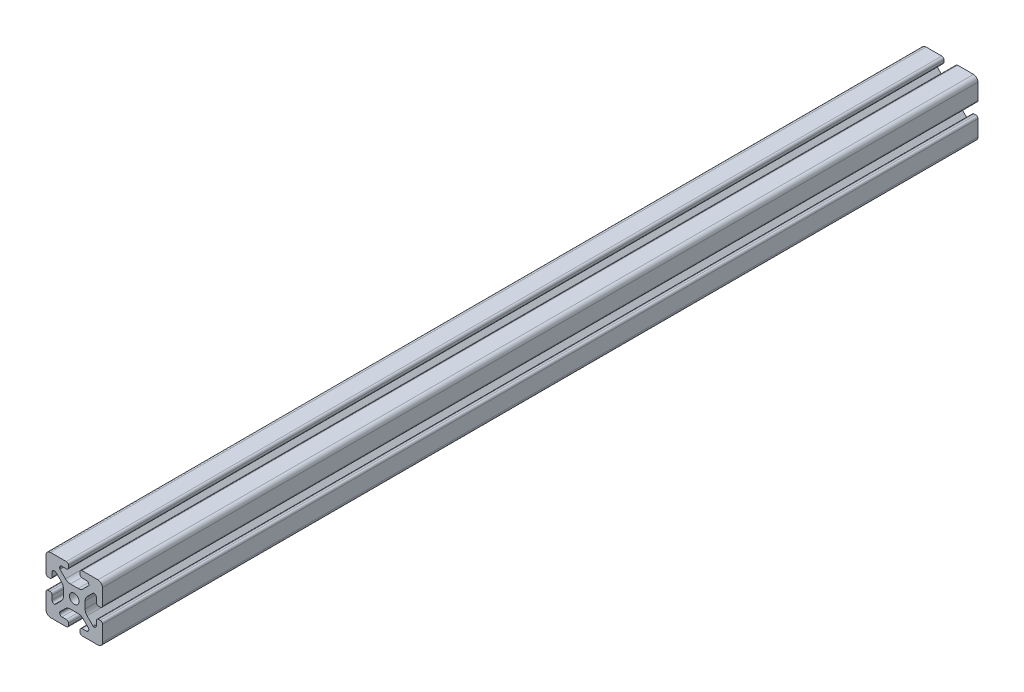
SolidWorks part; units mm, degrees
material "6061 Alloy"
ref_plane "Front Plane" through (0, 0, 0) normal (0, 0, 1) x (1, 0, 0)
ref_plane "Top Plane" through (0, 0, 0) normal (0, 1, 0) x (1, 0, 0)
ref_plane "Right Plane" through (0, 0, 0) normal (1, 0, 0) x (0, 0, -1)
sketch "Sketch1" plane through (0, 0, 0) normal (0, 0, 1) x (1, 0, 0)
  line L0 (0, 19.7407) -> (0, -19.7407) construction
  line L1 (19.0335, 0) -> (-20.7246, 0) construction
  line L2 (-8.715, -15.5246) -> (-5.63, -15.5246)
  line L3 (-10.285, -13.9546) -> (-10.285, -13.4925)
  line L4 (-6.2171, -9.1098) -> (-10.0624, -12.9551)
  line L5 (2.7773, -7.685) -> (-2.7773, -7.685)
  line L6 (10.0624, -12.9551) -> (6.2171, -9.1098)
  line L7 (10.285, -13.9546) -> (10.285, -13.4925)
  line L8 (5.63, -15.5246) -> (8.715, -15.5246)
  line L9 (4.06, -18.43) -> (4.06, -17.0946)
  line L10 (-4.06, -18.43) -> (-4.06, -17.0946)
  line L11 (15.68, -8.7154) -> (15.68, -5.63)
  line L12 (-14.11, -10.2854) -> (-13.8169, -10.2854)
  line L13 (20, -16.83) -> (20, -5.63)
  line L14 (20, 5.63) -> (20, 13.0011)
  line L15 (-16.83, 20) -> (-5.63, 20)
  line L16 (5.63, 20) -> (12.9796, 20)
  line L18 (-8.715, 15.5246) -> (-5.63, 15.5246)
  line L19 (-20, -17.0184) -> (-20, -5.7579)
  line L20 (-20, 5.573) -> (-20, 13.0045)
  line L21 (-15.68, -8.7154) -> (-15.68, -5.7579)
  line L23 (-16.6746, -20) -> (-5.63, -20)
  line L24 (5.63, -20) -> (13, -20)
  line L53 (14.11, -10.2854) -> (13.6201, -10.2854)
  line L54 (13.1637, -9.947) -> (9.0762, -5.8595)
  line L55 (7.685, -2.5008) -> (7.685, 2.5008)
  line L56 (9.0762, 5.8595) -> (13.2795, 10.0628)
  line L57 (13.8169, 10.2854) -> (14.11, 10.2854)
  line L58 (15.68, 8.7154) -> (15.68, 5.63)
  line L59 (17.25, 4.06) -> (18.43, 4.06)
  line L61 (20, 13.0011) -> (20, 16.83)
  line L62 (16.83, 20) -> (12.9796, 20)
  line L64 (4.06, 18.43) -> (4.06, 17.0946)
  line L65 (5.63, 15.5246) -> (8.715, 15.5246)
  line L66 (10.285, 13.9546) -> (10.285, 13.4925)
  line L67 (10.0624, 12.9551) -> (6.2171, 9.1098)
  line L68 (2.7773, 7.685) -> (-2.7773, 7.685)
  line L69 (-6.2171, 9.1098) -> (-10.0624, 12.9551)
  line L70 (-10.285, 13.4925) -> (-10.285, 13.9546)
  line L72 (-4.06, 17.0946) -> (-4.06, 18.43)
  line L75 (-20, 16.83) -> (-20, 13.0045)
  line L77 (-18.43, 4.003) -> (-17.25, 4.003)
  line L78 (-15.68, 5.573) -> (-15.68, 8.4757)
  line L79 (-14.0552, 10.0447) -> (-13.7199, 10.033)
  line L80 (-13.0405, 9.8238) -> (-9.0762, 5.8595)
  line L81 (-7.685, 2.5008) -> (-7.685, -2.5008)
  line L82 (-9.0762, -5.8595) -> (-13.2795, -10.0628)
  line L85 (-17.25, -4.1204) -> (-18.43, -4.1204)
  line L100 (13, -20) -> (16.83, -20)
  line L103 (18.43, -4.06) -> (17.25, -4.06)
  arc A0 (-5.63, -15.5246) -> (-4.06, -17.0946) centre (-5.63, -17.0946) cw
  arc A1 (-8.715, -15.5246) -> (-10.285, -13.9546) centre (-8.715, -13.9546) cw
  arc A2 (-10.285, -13.4925) -> (-10.0624, -12.9551) centre (-9.525, -13.4925) cw
  arc A3 (-6.2171, -9.1098) -> (-2.7773, -7.685) centre (-2.7773, -12.5496) cw
  arc A4 (2.7773, -7.685) -> (6.2171, -9.1098) centre (2.7773, -12.5496) cw
  arc A5 (10.0624, -12.9551) -> (10.285, -13.4925) centre (9.525, -13.4925) cw
  arc A6 (10.285, -13.9546) -> (8.715, -15.5246) centre (8.715, -13.9546) cw
  arc A7 (4.06, -17.0946) -> (5.63, -15.5246) centre (5.63, -17.0946) cw
  arc A8 (5.63, -20) -> (4.06, -18.43) centre (5.63, -18.43) cw
  arc A9 (-4.06, -18.43) -> (-5.63, -20) centre (-5.63, -18.43) cw
  circle A45 centre (0, 0) radius 3.4
  arc A46 (17.25, -4.06) -> (15.68, -5.63) centre (17.25, -5.63) ccw
  arc A47 (14.11, -10.2854) -> (15.68, -8.7154) centre (14.11, -8.7154) ccw
  arc A48 (13.1637, -9.947) -> (13.6201, -10.2854) centre (13.8117, -9.55) ccw
  arc A49 (7.685, -2.5008) -> (9.0762, -5.8595) centre (12.435, -2.5008) ccw
  arc A50 (9.0762, 5.8595) -> (7.685, 2.5008) centre (12.435, 2.5008) ccw
  arc A51 (13.8169, 10.2854) -> (13.2795, 10.0628) centre (13.8169, 9.5254) ccw
  arc A52 (15.68, 8.7154) -> (14.11, 10.2854) centre (14.11, 8.7154) ccw
  arc A53 (15.68, 5.63) -> (17.25, 4.06) centre (17.25, 5.63) ccw
  arc A54 (18.43, 4.06) -> (20, 5.63) centre (18.43, 5.63) ccw
  arc A55 (20, 16.83) -> (16.83, 20) centre (16.83, 16.83) ccw
  arc A56 (5.63, 20) -> (4.06, 18.43) centre (5.63, 18.43) ccw
  arc A57 (4.06, 17.0946) -> (5.63, 15.5246) centre (5.63, 17.0946) ccw
  arc A58 (10.285, 13.9546) -> (8.715, 15.5246) centre (8.715, 13.9546) ccw
  arc A59 (10.0624, 12.9551) -> (10.285, 13.4925) centre (9.525, 13.4925) ccw
  arc A60 (2.7773, 7.685) -> (6.2171, 9.1098) centre (2.7773, 12.5496) ccw
  arc A61 (-6.2171, 9.1098) -> (-2.7773, 7.685) centre (-2.7773, 12.5496) ccw
  arc A62 (-10.285, 13.4925) -> (-10.0624, 12.9551) centre (-9.525, 13.4925) ccw
  arc A63 (-8.715, 15.5246) -> (-10.285, 13.9546) centre (-8.715, 13.9546) ccw
  arc A64 (-5.63, 15.5246) -> (-4.06, 17.0946) centre (-5.63, 17.0946) ccw
  arc A65 (-4.06, 18.43) -> (-5.63, 20) centre (-5.63, 18.43) ccw
  arc A66 (-16.83, 20) -> (-20, 16.83) centre (-16.83, 16.83) ccw
  arc A67 (-20, 5.573) -> (-18.43, 4.003) centre (-18.43, 5.573) ccw
  arc A68 (-17.25, 4.003) -> (-15.68, 5.573) centre (-17.25, 5.573) ccw
  arc A69 (-14.0552, 10.0447) -> (-15.68, 8.4757) centre (-14.11, 8.4757) ccw
  arc A70 (-13.0405, 9.8238) -> (-13.7199, 10.033) centre (-13.5779, 9.2864) ccw
  arc A71 (-7.685, 2.5008) -> (-9.0762, 5.8595) centre (-12.435, 2.5008) ccw
  arc A72 (-9.0762, -5.8595) -> (-7.685, -2.5008) centre (-12.435, -2.5008) ccw
  arc A73 (-13.8169, -10.2854) -> (-13.2795, -10.0628) centre (-13.8169, -9.5254) ccw
  arc A74 (-15.68, -8.7154) -> (-14.11, -10.2854) centre (-14.11, -8.7154) ccw
  arc A75 (-15.68, -5.7579) -> (-17.25, -4.1204) centre (-17.2485, -5.6904) ccw
  arc A76 (-18.43, -4.1204) -> (-20, -5.7579) centre (-18.4315, -5.6904) ccw
  arc A77 (-20, -17.0184) -> (-16.6746, -20) centre (-16.8354, -16.8341) ccw
  arc A88 (16.83, -20) -> (20, -16.83) centre (16.83, -16.83) ccw
  arc A89 (20, -5.63) -> (18.43, -4.06) centre (18.43, -5.63) ccw
  dimension "D2" = 6.8
  dimension "D7" = 20.57
  dimension "D1" = 40
  dimension "D3" = 4.32
  dimension "D4" = 15.37
  dimension "D5" = 20
  dimension "D6" = 4.32
  dimension "D9" = 15.37
extrude "Extrude1" add sketch "Sketch1" against normal blind 620
equation "\"PinDiameter\"= 0"
equation "\"WallThickness\"= 0.5cm"
equation "\"BottomPlateX\"= 100cm"
equation "\"BottomPlateZ\"= 70cm"
equation "\"BottomPlateHoleD\"=((\"ArmPlateX\")^2+(\"ArmPlateDepth\")^2)^.5+ 10mm"
equation "\"ActuatorL\"= 35cm"
equation "\"ActuatorPinD\"= 6.35mm"
equation "\"ActuatorPinL\"= 15cm"
equation "\"Box-X\"= 40cm"
equation "\"Box-Z\"= 20cm"
equation "\"Box-Y\"= 30cm"
equation "\"ArmPlateThickness\"= 1cm"
equation "\"ArmPlateX\"= 50cm"
equation "\"ArmPlateDepth\"= 20cm"
equation "\"Arm1X\"= 5cm"
equation "\"Arm1L\"= 60cm"
equation "\"Arm2GAP\"= 5cm"
equation "\"Arm2L\"= 60cm"
equation "\"Arm2H\"= 5cm"
equation "\"Arm2Extension\"= 5cm"
equation "\"Arm3GAP\"= 5cm"
equation "\"Arm3L\"= 60cm"
equation "\"Arm3H\"= 5cm"
equation "\"Pin1-2L\"= \"Arm2GAP\" + (2 * \"WallThickness\")"
equation "\"Pin2-3L\"= \"Arm3GAP\" + (4 * \"WallThickness\")"
equation "\"DCMotor1D\"= 65mm"
equation "\"DCMotor1L\"= 215mm"
equation "\"DCMotor1ShaftL\"= 30mm"
equation "\"DCMotor2X\"= 68mm"
equation "\"DCMotor2D\"= 65mm"
equation "\"DCMotor2L\"= 215mm"
equation "\"DCMotor2ShaftL\"= 30mm"
equation "\"DCMotor2ShaftD\"= 15mm"
equation "\"BenchDepth\"= 5cm"
equation "\"BenchH\"= 10cm"
equation "\"BenchL\"= 15cm"
equation "\"PillowBlockW\"= 5cm"
equation "\"PillowBlockCenterH\"= \"DCMotor2X\"/2"
equation "\"EncoderRadius\"= 19mm"
equation "\"EncoderShaftL\"= 15mm"
equation "\"EncoderL\"= 33mm"
equation "\"EncoderHousingThickness\"= 7.5mm"
equation "\"TurntableID\"= 70mm"
equation "\"TurntableInner2*t\" = (\"TurntableOD\"-\"TurntableID\")*.25 - .5mm"
equation "\"TurntableInnerHoleRadius\"= \"TurntableID\"*.5 + \"TurntableInner2*t\"*.5"
equation "\"TurntableOD\"= 120mm"
equation "\"TurntableOuterHoleRadius\" = \"TurntableOD\"*.5 - ((\"TurntableOD\"-\"TurntableID\")*.25-.5mm)*.5"
equation "\"LENGTH@Extrude1\"=\"BottomPlateZ\"-80mm"
